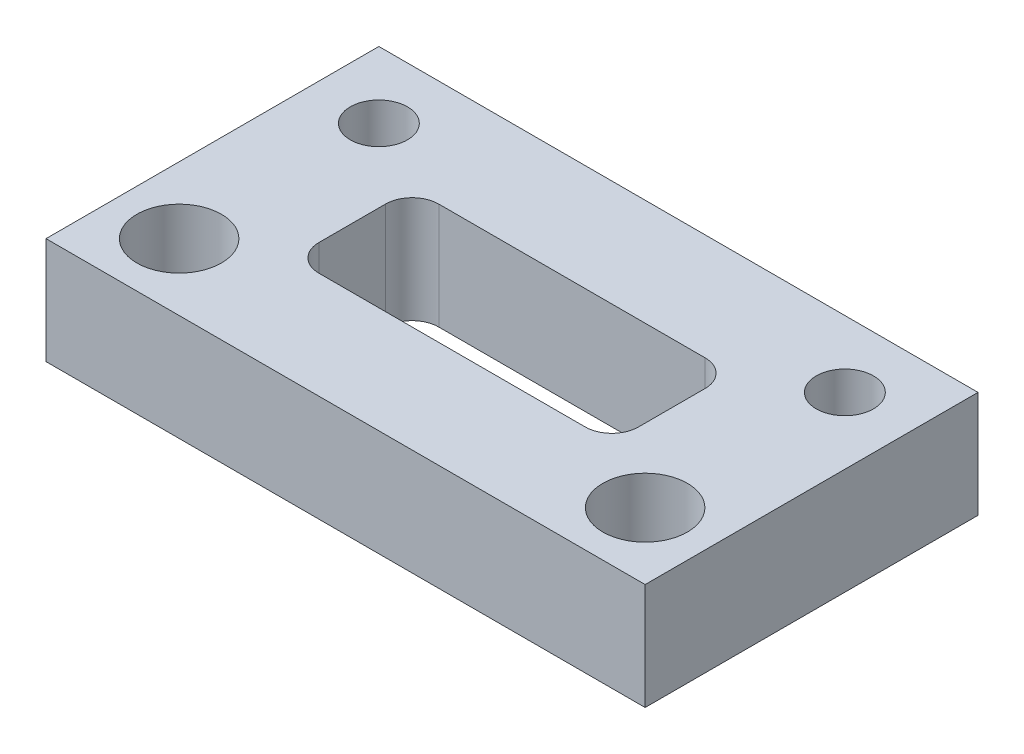
SolidWorks part; units mm, degrees
material "ABS"
ref_plane "前视基准面" through (0, 0, 0) normal (0, 0, 1) x (1, 0, 0)
ref_plane "上视基准面" through (0, 0, 0) normal (0, 1, 0) x (1, 0, 0)
ref_plane "右视基准面" through (0, 0, 0) normal (1, 0, 0) x (0, 0, -1)
sketch "草图1" plane through (0, 0, 0) normal (0, 1, 0) x (1, 0, 0)
  line L1 (22.5, -12.5) -> (-22.5, -12.5)
  line L2 (22.5, -12.5) -> (22.5, 12.5)
  line L3 (22.5, 12.5) -> (-22.5, 12.5)
  line L4 (-22.5, -12.5) -> (-22.5, 12.5)
  line L5 (22.5, -12.5) -> (-22.5, 12.5) construction
  line L6 (22.5, 12.5) -> (-22.5, -12.5) construction
  point P0 (0, 0)
  dimension "D1" = 45
  dimension "D2" = 25
extrude "凸台-拉伸1" add sketch "草图1" along normal blind 8
sketch "草图2" plane through (0, 8, 0) normal (0, 1, 0) x (1, 0, 0)
  line L1 (17.5, -7.5) -> (-17.5, -7.5) construction
  line L2 (17.5, -7.5) -> (17.5, 7.5) construction
  line L3 (17.5, 7.5) -> (-17.5, 7.5) construction
  line L4 (-17.5, -7.5) -> (-17.5, 7.5) construction
  line L5 (17.5, -7.5) -> (-17.5, 7.5) construction
  line L6 (17.5, 7.5) -> (-17.5, -7.5) construction
  circle A0 centre (-17.5, 7.5) radius 2.15
  circle A1 centre (17.5, 7.5) radius 2.15
  circle A2 centre (17.5, -7.5) radius 3.175
  circle A3 centre (-17.5, -7.5) radius 3.175
  point P0 (0, 0)
  dimension "D3" = 4.3
  dimension "D4" = 6.35
  dimension "D1" = 35
  dimension "D2" = 15
extrude "切除-拉伸1" cut sketch "草图2" against normal through all
sketch "草图3" plane through (0, 8, 0) normal (0, 1, 0) x (1, 0, 0)
  line L1 (12, -4.5) -> (-12, -4.5)
  line L2 (12, -4.5) -> (12, 4.5)
  line L3 (12, 4.5) -> (-12, 4.5)
  line L4 (-12, -4.5) -> (-12, 4.5)
  line L5 (12, -4.5) -> (-12, 4.5) construction
  line L6 (12, 4.5) -> (-12, -4.5) construction
  point P0 (0, 0)
  dimension "D1" = 24
  dimension "D2" = 9
extrude "切除-拉伸2" cut sketch "草图3" against normal through all
fillet "圆角1" radius 2 4 edges at (12, 4, -4.5) (12, 4, 4.5) (-12, 4, -4.5) (-12, 4, 4.5)
